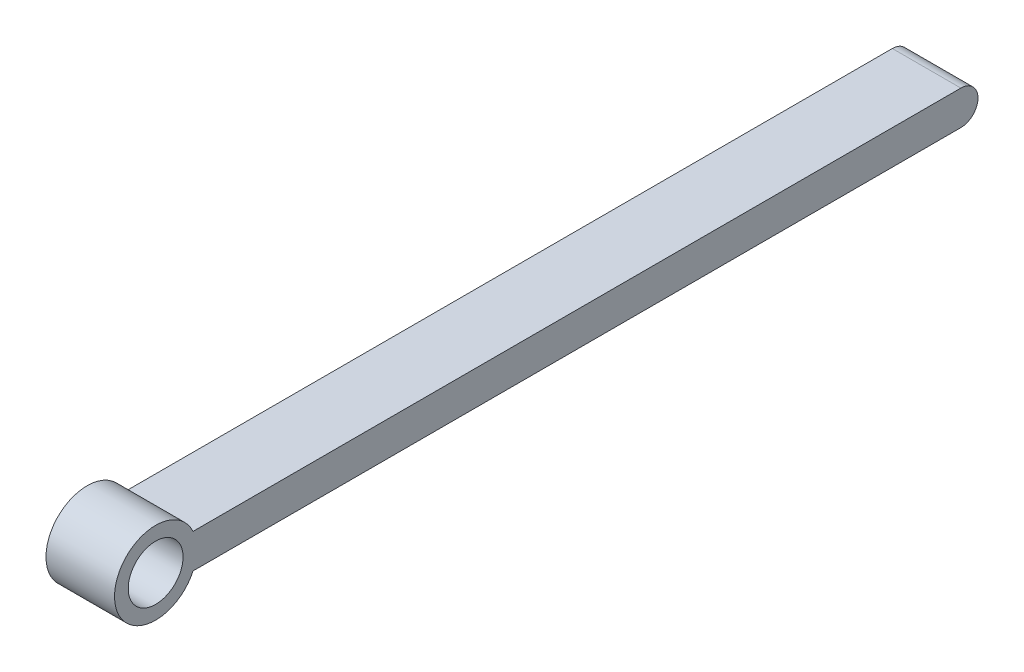
SolidWorks part; units mm, degrees
ref_plane "Front Plane" through (0, 0, 0) normal (0, 0, 1) x (1, 0, 0)
ref_plane "Top Plane" through (0, 0, 0) normal (0, 1, 0) x (1, 0, 0)
ref_plane "Right Plane" through (0, 0, 0) normal (1, 0, 0) x (0, 0, -1)
sketch "Sketch1" plane through (0, 0, 0) normal (1, 0, 0) x (0, 0, -1)
  line L0 (139.5728, 18.1245) -> (139.5728, -12.7028) construction
  line L1 (19.5728, 20.6245) -> (137.0728, 20.6245)
  line L2 (19.5728, 20.6245) -> (19.5728, 15.6245)
  line L3 (19.5728, 15.6245) -> (137.0728, 15.6245)
  line L4 (137.0728, 20.6245) -> (137.0728, 15.6245)
  line L5 (19.5728, 18.1245) -> (15.7388, 18.1245) construction
  circle A0 centre (19.5728, 18.1245) radius 4
  circle A1 centre (19.5728, 18.1245) radius 6
  arc A2 (137.0728, 20.6245) -> (137.0728, 15.6245) centre (137.0728, 18.1245) cw
  dimension "D1" = 8
  dimension "D2" = 2
  dimension "D3" = 120
  dimension "D4" = 5
extrude "Boss-Extrude1" add sketch "Sketch1" along normal blind 10 contours L1 A1 L3 A0 | L3 A1 L1 A0 | A1 L3 L4 L1 | A2 L4
